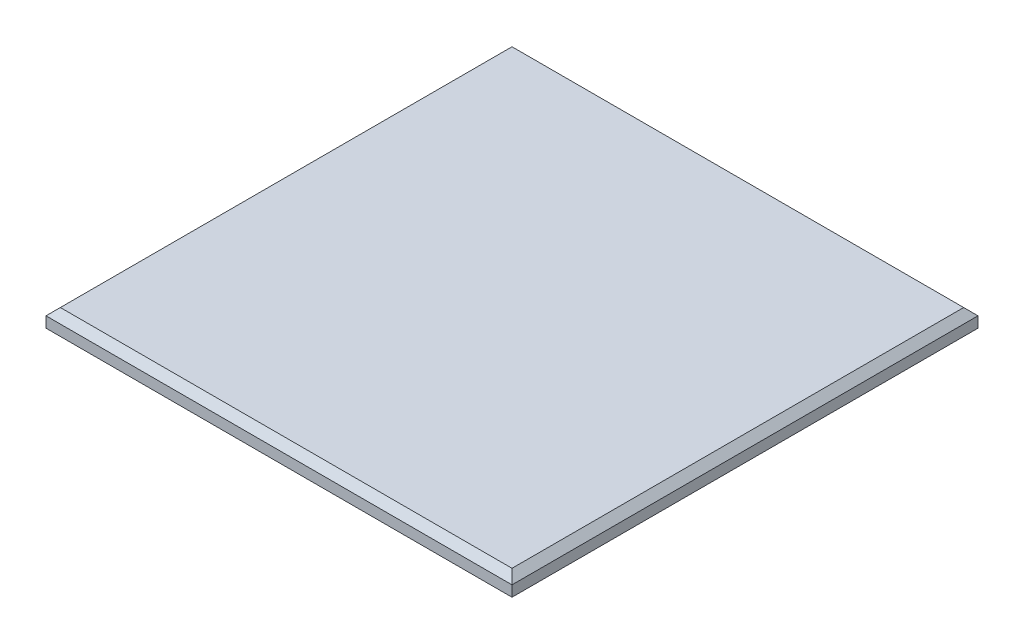
SolidWorks part; units mm, degrees
ref_plane "前视基准面" through (0, 0, 0) normal (0, 0, 1) x (1, 0, 0)
ref_plane "上视基准面" through (0, 0, 0) normal (0, 1, 0) x (1, 0, 0)
ref_plane "右视基准面" through (0, 0, 0) normal (1, 0, 0) x (0, 0, -1)
sketch "草图1" plane through (0, 0, 0) normal (0, 1, 0) x (1, 0, 0)
  line L1 (-65.5018, -64.8834) -> (64.4982, -64.8834)
  line L2 (-65.5018, -64.8834) -> (-65.5018, 65.1166)
  line L3 (-65.5018, 65.1166) -> (64.4982, 65.1166)
  line L4 (64.4982, -64.8834) -> (64.4982, 65.1166)
  dimension "D1" = 130
  dimension "D2" = 130
extrude "凸台-拉伸1" add sketch "草图1" along normal blind 5
sketch "草图2" plane through (0, 0, 0) normal (0, -1, 0) x (1, 0, 0)
  line L0 (21.235, 8.9726) -> (22.235, 8.9726)
  line L1 (-22.235, -8.9726) -> (-21.235, -8.9726)
  line L2 (-22.235, -8.9726) -> (-22.235, 8.9726)
  line L3 (-22.235, 8.9726) -> (-21.235, 8.9726)
  line L4 (22.235, -8.9726) -> (22.235, 8.9726)
  line L5 (-22.235, -8.9726) -> (-21.235, -8.569) construction
  line L6 (-22.235, 8.9726) -> (-21.235, 8.569) construction
  line L8 (-21.235, -8.9726) -> (-21.235, 8.9726)
  line L10 (21.235, -8.9726) -> (21.235, 8.9726)
  line L13 (21.235, -8.569) -> (22.235, -8.9726) construction
  line L14 (21.235, 8.569) -> (22.235, 8.9726) construction
  line L15 (21.235, -8.9726) -> (22.235, -8.9726)
  point P0 (0, 0)
  point P6 (0, 0)
  dimension "D1" = 44.47
  dimension "D2" = 42.47
extrude "凸台-拉伸2" add sketch "草图2" along normal blind 8
sketch "草图3" plane through (-22.235, 0, 0) normal (-1, 0, 0) x (0, 0, 1)
  circle A0 centre (0, -3.7844) radius 2.5
  dimension "D1" = 5
extrude "凸台-拉伸3" add sketch "草图3" against normal blind 43
chamfer "倒角1" distance 2 angle 45 4 edges at (-0.5018, 5, -65.1166) (64.4982, 5, -0.1166) (-0.5018, 5, 64.8834) (-65.5018, 5, -0.1166)
